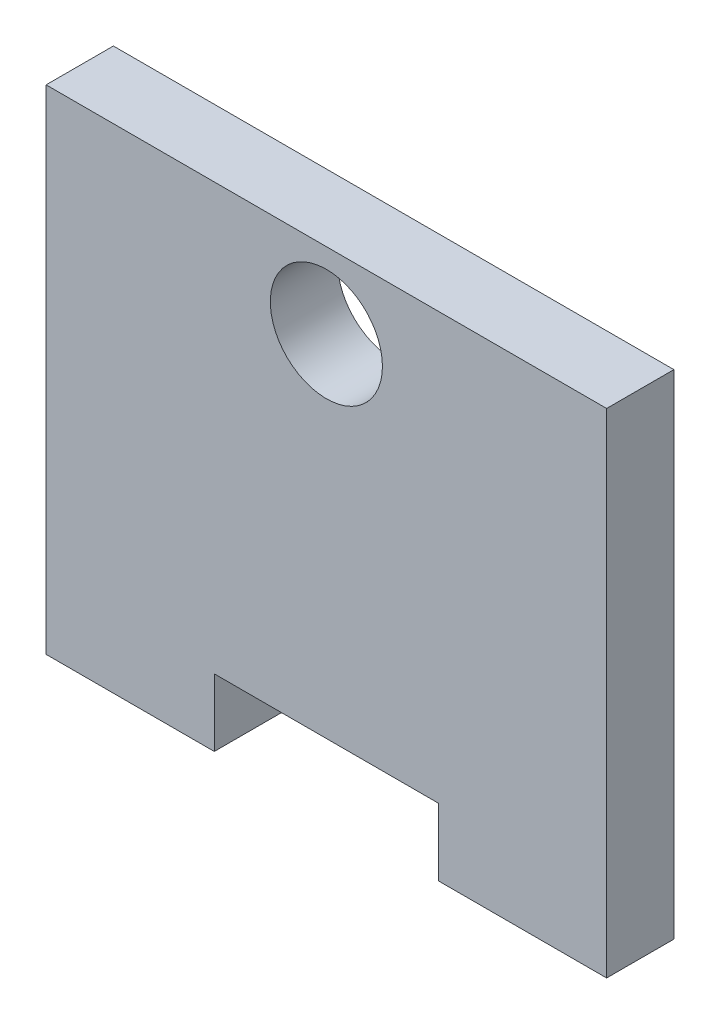
SolidWorks part; units mm, degrees
ref_plane "Plan de face" through (0, 0, 0) normal (0, 0, 1) x (1, 0, 0)
ref_plane "Plan de dessus" through (0, 0, 0) normal (0, 1, 0) x (1, 0, 0)
ref_plane "Plan de droite" through (0, 0, 0) normal (1, 0, 0) x (0, 0, -1)
sketch "Esquisse1" plane through (0, 0, 0) normal (0, 0, 1) x (1, 0, 0)
  line L0 (15, 0) -> (35, 0)
  line L1 (50, 0) -> (50, 38)
  line L2 (50, 38) -> (0, 38)
  line L3 (0, 38) -> (0, 0)
  line L4 (0, 19) -> (50, 19) construction
  line L12 (25, 43.5) -> (25, 19) construction
  line L14 (0, 0) -> (0, -6)
  line L15 (0, -6) -> (15, -6)
  line L16 (15, 0) -> (15, -6)
  line L18 (50, 0) -> (50, -6)
  line L19 (50, -6) -> (35, -6)
  line L20 (35, 0) -> (35, -6)
  circle A5 centre (25, 31.25) radius 5
  dimension "D5" = 6
  dimension "D6" = 6
  dimension "D3" = 10
  dimension "D1" = 38
  dimension "D2" = 50
  dimension "D4" = 31.25
  dimension "D7" = 15
  dimension "D8" = 15
extrude "Boss.-Extru.1" add sketch "Esquisse1" along normal blind 6
